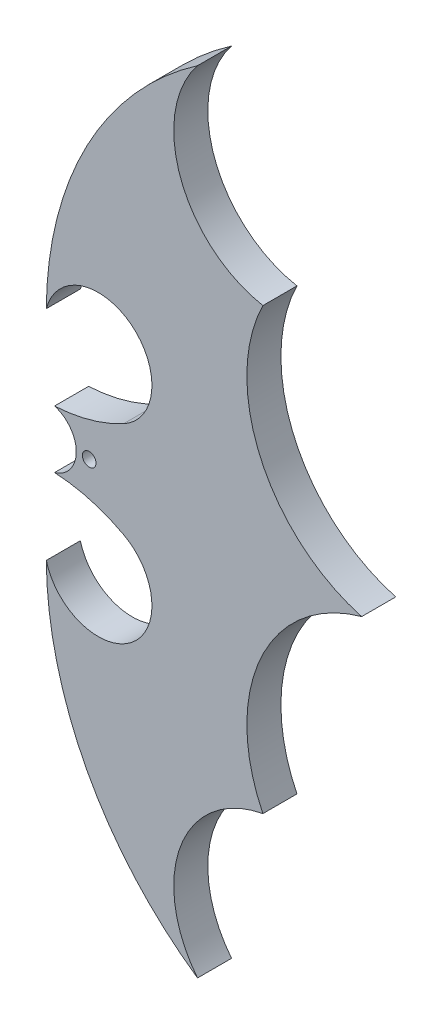
SolidWorks part; units mm, degrees
ref_plane "Front Plane" through (0, 0, 0) normal (1, 0, 0) x (0, 1, 0)
ref_plane "Top Plane" through (0, 0, 0) normal (0, 0, 1) x (0, 1, 0)
ref_plane "Right Plane" through (0, 0, 0) normal (0, 1, 0) x (-1, 0, 0)
sketch "Sketch1" plane through (0, 0, 0) normal (0, 0, 1) x (0, 1, 0)
  line L0 (0, -17.1593) -> (0, 20.0653) construction
  arc A0 (0, 0) -> (32.3, 14.5) centre (22.1637, -6.1459) cw
  arc A1 (32.3, 14.5) -> (58, 24.1) centre (48.0321, 11.5844) cw
  arc A2 (58, 24.1) -> (16, 46.3) centre (15.6464, -5.1988) ccw
  arc A6 (0, 0) -> (-32.3, 14.5) centre (-22.1637, -6.1459) ccw
  arc A9 (-58, 24.1) -> (-16, 46.3) centre (-15.6464, -5.1988) cw
  arc A10 (-32.3, 14.5) -> (-58, 24.1) centre (-48.0321, 11.5844) ccw
  arc A11 (16, 46.3) -> (7.0553, 34.9465) centre (14, 38.6754) cw
  arc A12 (7.0553, 34.9465) -> (4.2305, 45.0905) centre (28.2, 46.3) cw
  arc A13 (4.2305, 45.0905) -> (-4.2305, 45.0905) centre (0, 46.3) cw
  arc A14 (-16, 46.3) -> (-7.0553, 34.9465) centre (-14, 38.6754) ccw
  arc A15 (-7.0553, 34.9465) -> (-4.2305, 45.0905) centre (-28.2, 46.3) ccw
  dimension "D1" = 23
  dimension "D2" = 16
  dimension "D5" = 51.5
  dimension "D6" = 32
  dimension "D7" = 28.2
  dimension "D8" = 14
  dimension "D12" = 46.3
  dimension "D13" = 24
  dimension "D14" = 4.4
  dimension "D3" = 14.5
  dimension "D4" = 9.6
  dimension "D9" = 46.3
  dimension "D10" = 32.3
  dimension "D11" = 58
extrude "Boss-Extrude1" add sketch "Sketch1" along normal blind 5
sketch "Sketch2" plane through (0, 0, 5) normal (0, 0, 1) x (1, 0, 0)
  circle A0 centre (-40, 0) radius 1
  dimension "D1" = 2
  dimension "D2" = 40
extrude "Cut-Extrude2" cut sketch "Sketch2" against normal blind 5
